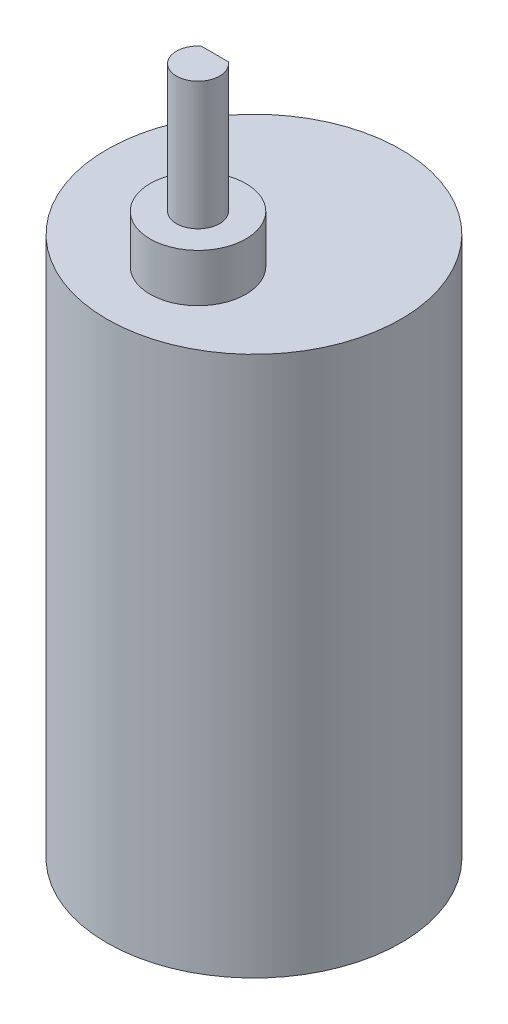
SolidWorks part; units mm, degrees
ref_plane "Front Plane" through (0, 0, 0) normal (0, 0, 1) x (1, 0, 0)
ref_plane "Top Plane" through (0, 0, 0) normal (0, 1, 0) x (1, 0, 0)
ref_plane "Right Plane" through (0, 0, 0) normal (1, 0, 0) x (0, 0, -1)
sketch "Sketch1" plane through (0, 0, 0) normal (0, 1, 0) x (1, 0, 0)
  circle A0 centre (0, 0) radius 18.4
  dimension "D1" = 36.8
extrude "Boss-Extrude1" add sketch "Sketch1" along normal blind 67.6
sketch "Sketch2" plane through (0, 67.6, 0) normal (0, 1, 0) x (1, 0, 0)
  circle A0 centre (0, -7) radius 6
  dimension "D1" = 12
  dimension "D2" = 7
extrude "Boss-Extrude2" add sketch "Sketch2" along normal blind 6
sketch "Sketch3" plane through (0, 73.6, 0) normal (0, 1, 0) x (1, 0, 0)
  line L0 (-1.6971, -4.9) -> (1.6971, -4.9)
  arc A0 (-1.6971, -4.9) -> (1.6971, -4.9) centre (0, -7) ccw
  dimension "D1" = 5.4
  dimension "D2" = 2.1
extrude "Boss-Extrude3" add sketch "Sketch3" along normal blind 22 from surface at -6 starting at face at (0, 67.6, 13)
